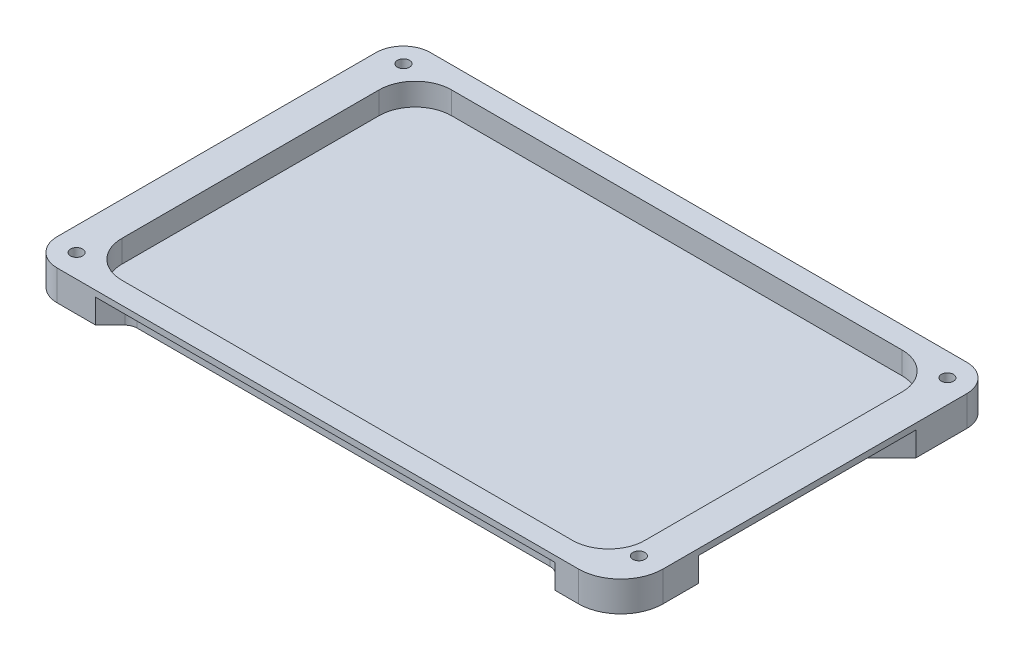
SolidWorks part; units mm, degrees
ref_plane "Front Plane" through (0, 0, 0) normal (0, 0, 1) x (1, 0, 0)
ref_plane "Top Plane" through (0, 0, 0) normal (0, 1, 0) x (1, 0, 0)
ref_plane "Right Plane" through (0, 0, 0) normal (1, 0, 0) x (0, 0, -1)
sketch "Sketch5" plane through (0, 0, 0) normal (0, 1, 0) x (1, 0, 0)
  line L1 (-44.375, -30.875) -> (41.875, -30.875)
  line L2 (-48.875, -26.375) -> (-48.875, 26.375)
  line L3 (-44.375, 30.875) -> (44.375, 30.875)
  line L4 (48.875, -23.875) -> (48.875, 26.375)
  line L5 (-48.875, -30.875) -> (48.875, 30.875) construction
  line L6 (-48.875, 30.875) -> (48.875, -30.875) construction
  arc A0 (48.875, 26.375) -> (44.375, 30.875) centre (44.375, 26.375) ccw
  arc A1 (-44.375, 30.875) -> (-48.875, 26.375) centre (-44.375, 26.375) ccw
  arc A2 (-48.875, -26.375) -> (-44.375, -30.875) centre (-44.375, -26.375) ccw
  arc A3 (41.875, -30.875) -> (48.875, -23.875) centre (41.875, -23.875) ccw
  point P0 (0, 0)
  dimension "D3" = 4.5
  dimension "D4" = 7
  dimension "D1" = 97.75
  dimension "D2" = 61.75
extrude "Boss-Extrude2" add sketch "Sketch5" along normal blind 5
sketch "Sketch6" plane through (0, 0, 0) normal (0, -1, 0) x (1, 0, 0)
  line L0 (0, 30.89) -> (0, -30.875) construction
  line L2 (44.375, -30.875) -> (-44.375, -30.875) construction
  line L3 (-48.875, 0) -> (48.85, 0) construction
  line L4 (-48.875, -26.375) -> (-48.875, 26.375) construction
  line L6 (-47.975, 26.375) -> (-47.975, 19.975)
  line L7 (-45.9859, 18.557) -> (-39.9859, 20.6263)
  line L8 (-38.975, 22.0444) -> (-38.975, 28.475)
  line L9 (-40.475, 29.975) -> (-44.375, 29.975)
  line L10 (40.475, 29.975) -> (41.875, 29.975)
  line L11 (38.975, 22.0444) -> (38.975, 28.475)
  line L12 (45.9859, 18.557) -> (39.9859, 20.6263)
  line L13 (47.975, 23.875) -> (47.975, 19.975)
  line L14 (47.975, -26.375) -> (47.975, -19.975)
  line L15 (45.9859, -18.557) -> (39.9859, -20.6263)
  line L16 (38.975, -22.0444) -> (38.975, -28.475)
  line L17 (40.475, -29.975) -> (44.375, -29.975)
  line L18 (-40.475, -29.975) -> (-44.375, -29.975)
  line L19 (-38.975, -22.0444) -> (-38.975, -28.475)
  line L20 (-45.9859, -18.557) -> (-39.9859, -20.6263)
  line L21 (-47.975, -26.375) -> (-47.975, -19.975)
  arc A0 (-47.975, 26.375) -> (-44.375, 29.975) centre (-44.375, 26.375) cw
  arc A1 (-44.375, 30.875) -> (-48.875, 26.375) centre (-44.375, 26.375) ccw construction
  arc A2 (-38.975, 22.0444) -> (-39.9859, 20.6263) centre (-40.475, 22.0444) cw
  arc A3 (-40.475, 29.975) -> (-38.975, 28.475) centre (-40.475, 28.475) cw
  arc A4 (-47.975, 19.975) -> (-45.9859, 18.557) centre (-46.475, 19.975) ccw
  arc A5 (47.975, 19.975) -> (45.9859, 18.557) centre (46.475, 19.975) cw
  arc A6 (40.475, 29.975) -> (38.975, 28.475) centre (40.475, 28.475) ccw
  arc A7 (38.975, 22.0444) -> (39.9859, 20.6263) centre (40.475, 22.0444) ccw
  arc A8 (47.975, 23.875) -> (41.875, 29.975) centre (41.875, 23.875) ccw
  arc A9 (47.975, -26.375) -> (44.375, -29.975) centre (44.375, -26.375) cw
  arc A10 (38.975, -22.0444) -> (39.9859, -20.6263) centre (40.475, -22.0444) cw
  arc A11 (40.475, -29.975) -> (38.975, -28.475) centre (40.475, -28.475) cw
  arc A12 (47.975, -19.975) -> (45.9859, -18.557) centre (46.475, -19.975) ccw
  arc A13 (-47.975, -19.975) -> (-45.9859, -18.557) centre (-46.475, -19.975) cw
  arc A14 (-40.475, -29.975) -> (-38.975, -28.475) centre (-40.475, -28.475) ccw
  arc A15 (-38.975, -22.0444) -> (-39.9859, -20.6263) centre (-40.475, -22.0444) ccw
  arc A16 (-47.975, -26.375) -> (-44.375, -29.975) centre (-44.375, -26.375) ccw
  arc A17 (48.875, 23.875) -> (41.875, 30.875) centre (41.875, 23.875) ccw construction
  point P2 (-46.475, 18.475)
  point P3 (0, 0)
  point P25 (-38.975, 20.975)
  point P28 (-38.975, 29.975)
  point P31 (-47.975, 17.871)
  dimension "D1" = 3.6
  dimension "D2" = 0.9
  dimension "D6" = 1.5
  dimension "D7" = 360
  dimension "D9" = 77.95
  dimension "D3" = 9
  dimension "D4" = 9
  dimension "D5" = 11.5
  dimension "D8" = 3.9
  dimension "D10" = 37.1139
sketch "Sketch10" plane through (0, 0, 0) normal (0, -1, 0) x (1, 0, 0)
  line L0 (-48.875, 18) -> (-44.4608, 13.5858)
  line L1 (-48.875, -26.375) -> (-48.875, 26.375) construction
  line L2 (-43.875, 12.1716) -> (-43.875, -12.1716)
  line L3 (-44.4608, -13.5858) -> (-48.875, -18)
  line L4 (-48.875, -18) -> (-48.875, 18)
  line L5 (-48.875, 0) -> (48.875, 0) construction
  line L6 (48.875, 23.875) -> (48.875, -26.375) construction
  line L7 (0, 30.89) -> (0, -30.875) construction
  line L8 (48.875, -18) -> (48.875, 18)
  line L9 (44.375, -30.875) -> (-44.375, -30.875) construction
  line L10 (-38, -30.875) -> (-35.5858, -28.4608)
  line L11 (-34.1716, -27.875) -> (34.1716, -27.875)
  line L12 (35.5858, -28.4608) -> (38, -30.875)
  line L13 (-38, -30.875) -> (38, -30.875)
  line L14 (-38, 30.875) -> (38, 30.875)
  line L15 (35.5858, 28.4608) -> (38, 30.875)
  line L16 (-34.1716, 27.875) -> (34.1716, 27.875)
  line L17 (-38, 30.875) -> (-35.5858, 28.4608)
  line L60 (44.4608, -13.5858) -> (48.875, -18)
  line L61 (43.875, 12.1716) -> (43.875, -12.1716)
  line L62 (48.875, 18) -> (44.4608, 13.5858)
  arc A0 (-43.875, -12.1716) -> (-44.4608, -13.5858) centre (-45.875, -12.1716) cw
  arc A1 (-44.4608, 13.5858) -> (-43.875, 12.1716) centre (-45.875, 12.1716) cw
  arc A2 (35.5858, -28.4608) -> (34.1716, -27.875) centre (34.1716, -29.875) ccw
  arc A3 (-34.1716, -27.875) -> (-35.5858, -28.4608) centre (-34.1716, -29.875) ccw
  arc A4 (-34.1716, 27.875) -> (-35.5858, 28.4608) centre (-34.1716, 29.875) cw
  arc A5 (35.5858, 28.4608) -> (34.1716, 27.875) centre (34.1716, 29.875) cw
  arc A17 (44.4608, 13.5858) -> (43.875, 12.1716) centre (45.875, 12.1716) ccw
  arc A18 (43.875, -12.1716) -> (44.4608, -13.5858) centre (45.875, -12.1716) ccw
  dimension "D4" = 2
  dimension "D8" = 2
  dimension "D1" = 5
  dimension "D2" = 135
  dimension "D3" = 36
  dimension "D5" = 76
  dimension "D6" = 135
  dimension "D7" = 3
extrude "Cut-Extrude2" cut sketch "Sketch10" against normal blind 4
sketch "Sketch11" plane through (0, 4, 0) normal (0, -1, 0) x (1, 0, 0)
  line L0 (-35.5858, -28.4608) -> (-38, -30.875) construction
  line L1 (-38, 30.875) -> (-35.5858, 28.4608) construction
  line L2 (-34.1716, 27.875) -> (34.1716, 27.875) construction
  line L3 (35.5858, 28.4608) -> (38, 30.875) construction
  line L4 (38, -30.875) -> (35.5858, -28.4608) construction
  line L5 (34.1716, -27.875) -> (-34.1716, -27.875) construction
  line L6 (-35.5858, -28.4608) -> (-36.5, -29.375)
  line L7 (-36.5, 29.375) -> (-35.5858, 28.4608)
  line L8 (-34.1716, 27.875) -> (34.1716, 27.875)
  line L9 (35.5858, 28.4608) -> (36.5, 29.375)
  line L10 (36.5, -29.375) -> (35.5858, -28.4608)
  line L11 (34.1716, -27.875) -> (-34.1716, -27.875)
  line L12 (-36.5, -29.375) -> (36.5, -29.375)
  line L13 (-36.5, 29.375) -> (36.5, 29.375)
  line L14 (0, -27.875) -> (0, -29.375) construction
  line L15 (0, 29.375) -> (0, 27.875) construction
  arc A0 (-34.1716, -27.875) -> (-35.5858, -28.4608) centre (-34.1716, -29.875) ccw construction
  arc A1 (34.1716, 27.875) -> (35.5858, 28.4608) centre (34.1716, 29.875) ccw construction
  arc A2 (-35.5858, 28.4608) -> (-34.1716, 27.875) centre (-34.1716, 29.875) ccw construction
  arc A3 (35.5858, -28.4608) -> (34.1716, -27.875) centre (34.1716, -29.875) ccw construction
  arc A4 (-34.1716, -27.875) -> (-35.5858, -28.4608) centre (-34.1716, -29.875) ccw
  arc A5 (34.1716, 27.875) -> (35.5858, 28.4608) centre (34.1716, 29.875) ccw
  arc A6 (-35.5858, 28.4608) -> (-34.1716, 27.875) centre (-34.1716, 29.875) ccw
  arc A7 (35.5858, -28.4608) -> (34.1716, -27.875) centre (34.1716, -29.875) ccw
  dimension "D1" = 1.5
extrude "Boss-Extrude4" add sketch "Sketch11" along normal blind 1.2
extrude "Cut-Extrude5" cut sketch "Sketch6" against normal blind 1
sketch "Sketch13" plane through (0, 1, 0) normal (0, -1, 0) x (1, 0, 0)
  line L0 (0, 0) -> (-55.3724, 0) construction
  line L1 (0, 0) -> (0, 38.9927) construction
  circle A5 centre (45, 24) radius 1 construction
  circle A8 centre (-45, 27.04) radius 0.8 construction
  circle A9 centre (-45, 27.04) radius 1
  circle A11 centre (-45, -27.04) radius 1
  circle A14 centre (45, -27.04) radius 1
  circle A16 centre (45, 24) radius 1
  circle A17 centre (45, 24) radius 0.8 construction
  circle A18 centre (-45, 27.04) radius 0.8 construction
  circle A19 centre (-45, 27.04) radius 0.8 construction
  point P2 (0, 0)
  point P5 (0, 0)
  point P8 (0, 0)
  point P11 (0, 0)
  point P21 (0, 0)
  point P22 (0, 0)
  point P23 (0, 0)
  point P25 (0, 0)
  dimension "D1" = 2
  dimension "D2" = 0.2
  dimension "D3" = 55.3724
  dimension "D5" = 90.0513
  dimension "D6" = 0.2
extrude "Cut-Extrude6" cut sketch "Sketch13" against normal through all
sketch "Sketch16" plane through (0, 5, 0) normal (0, 1, 0) x (1, 0, 0)
  line L10 (-48.875, 26.375) -> (-48.875, -26.375) construction
  line L11 (-48.875, 0) -> (48.875, 0) construction
  line L12 (48.875, -23.875) -> (48.875, 26.375) construction
  line L13 (0, 30.875) -> (0, -30.875) construction
  line L14 (44.375, 30.875) -> (-44.375, 30.875) construction
  line L15 (-44.375, -30.875) -> (41.875, -30.875) construction
  line L17 (-37.275, 27.275) -> (37.275, 27.275)
  line L18 (-43.275, 21.275) -> (-43.275, -21.275)
  line L19 (-37.275, -27.275) -> (37.275, -27.275)
  line L20 (43.275, 21.275) -> (43.275, -21.275)
  line L21 (-43.275, 27.275) -> (43.275, -27.275) construction
  line L22 (-43.275, -27.275) -> (43.275, 27.275) construction
  line L23 (-34.1716, -27.875) -> (34.1716, -27.875) construction
  line L24 (-43.875, 12.1716) -> (-43.875, -12.1716) construction
  line L25 (-34.1716, -27.875) -> (34.1716, -27.875) construction
  line L26 (-43.875, 12.1716) -> (-43.875, -12.1716) construction
  arc A0 (37.275, -27.275) -> (43.275, -21.275) centre (37.275, -21.275) ccw
  arc A1 (43.275, 21.275) -> (37.275, 27.275) centre (37.275, 21.275) ccw
  arc A2 (-37.275, 27.275) -> (-43.275, 21.275) centre (-37.275, 21.275) ccw
  arc A3 (-43.275, -21.275) -> (-37.275, -27.275) centre (-37.275, -21.275) ccw
  point P1 (0, 0)
  dimension "D3" = 1.2
  dimension "D2" = 1.2
  dimension "D4" = 6
extrude "Cut-Extrude10" cut sketch "Sketch16" against normal blind 3.7
